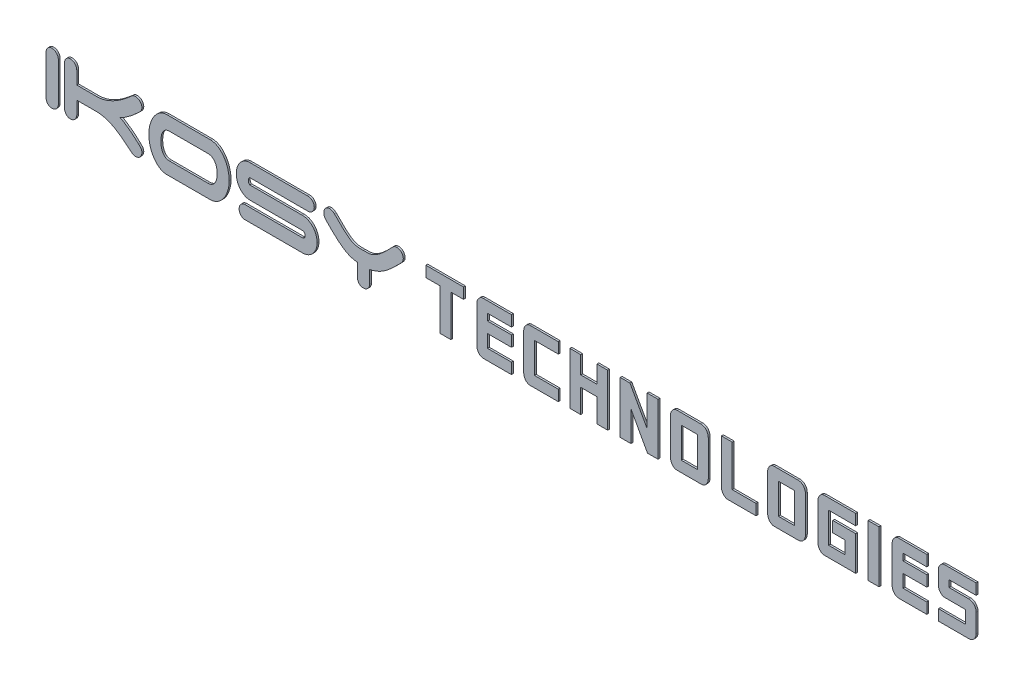
SolidWorks part; units mm, degrees
ref_plane "Front Plane" through (0, 0, 0) normal (0, 0, 1) x (1, 0, 0)
ref_plane "Top Plane" through (0, 0, 0) normal (0, 1, 0) x (1, 0, 0)
ref_plane "Right Plane" through (0, 0, 0) normal (1, 0, 0) x (0, 0, -1)
sketch "Text Sketch" plane through (0, 0, 0) normal (0, 0, 1) x (1, 0, 0)
  line L0 (158.0617, 381.3205) -> (790.3087, 381.3205) construction
  line L1 (-223.1193, 25.1941) -> (209.7014, 25.1941) construction
  line L2 (107.3834, 18.9017) -> (536.9168, 18.9017) construction
  text T0 "ikosy" font "Space Age" height 2.8
  text T1 "TECHNOLOGIES" font "Alien Encounters Solid" height 2.8
  point P8 (0, 0)
  dimension "D1" = 0.15
  dimension "D2" = 0.4
  dimension "D3" = 20.5
extrude "Text Extrude" add sketch "Text Sketch" along normal blind 0.1
